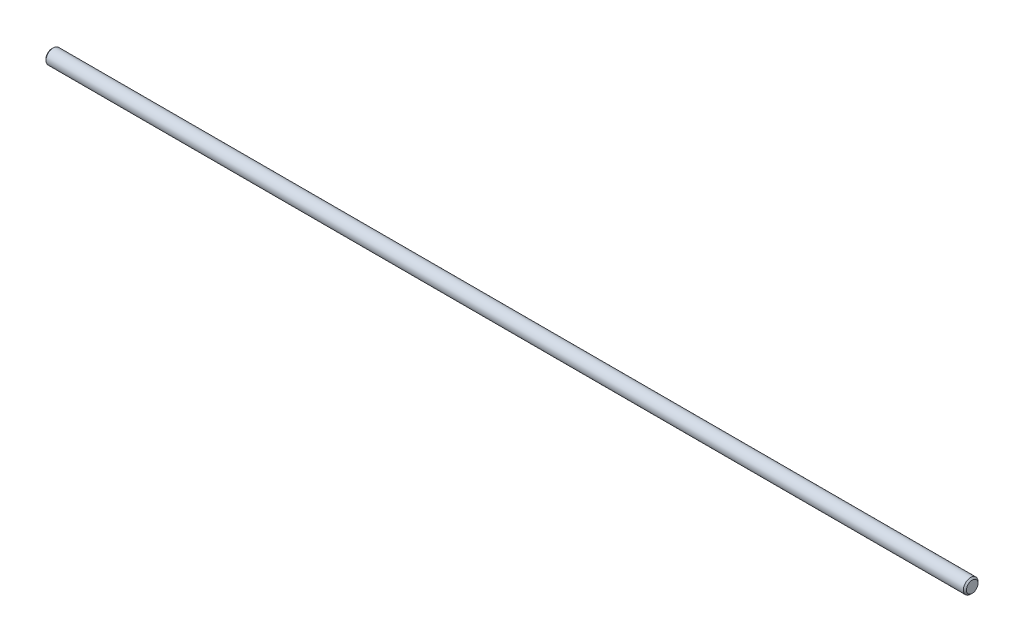
SolidWorks part; units mm, degrees
material "AISI Type A2 Tool Steel"
ref_plane "Front Plane" through (0, 0, 0) normal (0, 0, 1) x (1, 0, 0)
ref_plane "Top Plane" through (0, 0, 0) normal (0, 1, 0) x (1, 0, 0)
ref_plane "Right Plane" through (0, 0, 0) normal (1, 0, 0) x (0, 0, -1)
sketch "Sketch1" plane through (0, 0, 0) normal (1, 0, 0) x (0, 0, -1)
  circle A0 centre (0, 0) radius 4.7625
  dimension "D1" = 9.525
extrude "Boss-Extrude1" add sketch "Sketch1" along normal mid plane 600
chamfer "Chamfer1" distance 1 angle 45 2 edges at (300, 0, -4.7625) (-300, 0, -4.7625)
